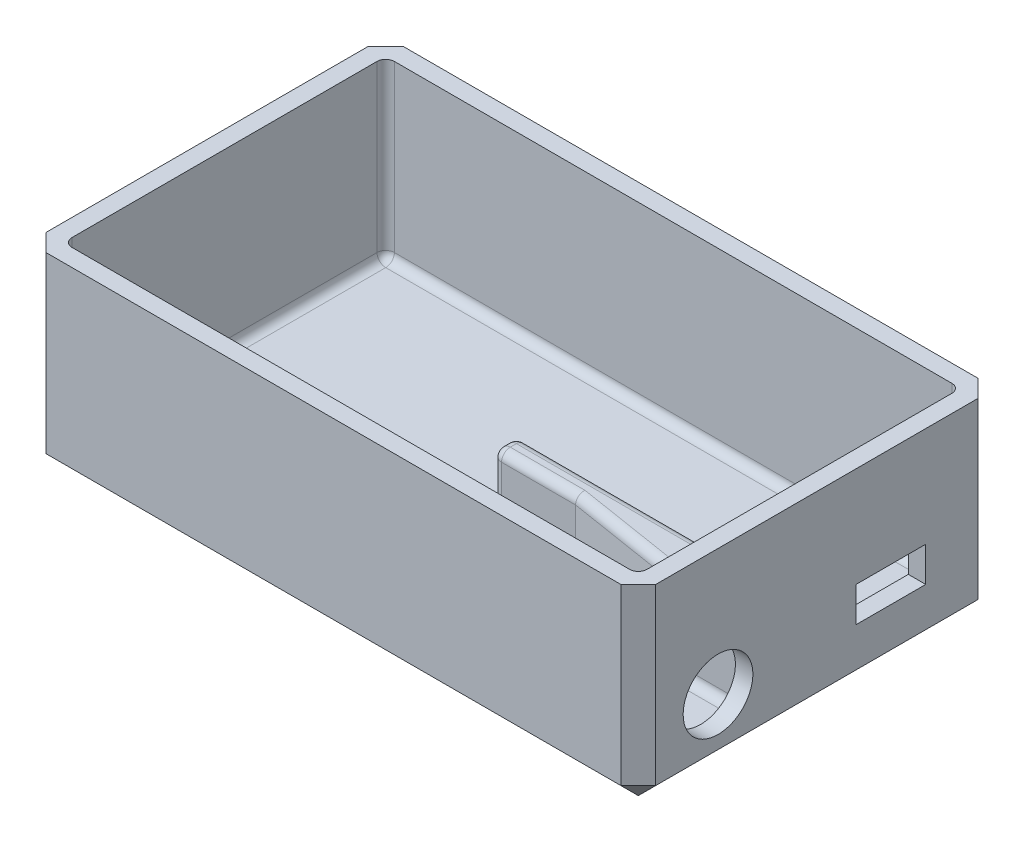
SolidWorks part; units mm, degrees
ref_plane "Plan de face" through (0, 0, 0) normal (0, 0, 1) x (1, 0, 0)
ref_plane "Plan de dessus" through (0, 0, 0) normal (0, 1, 0) x (1, 0, 0)
ref_plane "Plan de droite" through (0, 0, 0) normal (1, 0, 0) x (0, 0, -1)
sketch "Esquisse1" plane through (0, 0, 0) normal (0, 1, 0) x (1, 0, 0)
  line L1 (-35, 20.5) -> (35, 20.5)
  line L2 (-35, 20.5) -> (-35, -20.5)
  line L3 (-35, -20.5) -> (35, -20.5)
  line L4 (35, 20.5) -> (35, -20.5)
  line L5 (-35, 20.5) -> (35, -20.5) construction
  line L6 (-35, -20.5) -> (35, 20.5) construction
  point P0 (0, 0)
  dimension "D1" = 41
  dimension "D2" = 70
extrude "Boss.-Extru.1" add sketch "Esquisse1" along normal blind 22
shell "Coque1" thickness 2
sketch "Esquisse2" plane through (0, 2, 0) normal (0, 1, 0) x (1, 0, 0)
  line L0 (33, -16.5) -> (24, -16.5)
  line L1 (33, -18.5) -> (33, 18.5) construction
  line L2 (24, -16.5) -> (11.5, -18.5)
  line L3 (-33, -18.5) -> (33, -18.5) construction
  line L4 (11.5, -18.5) -> (33, -18.5)
  line L5 (33, -18.5) -> (33, -16.5)
  line L6 (33, -6.2) -> (24, -6.2)
  line L7 (24, -6.2) -> (11.5, -4.2)
  line L9 (33, -1.5) -> (33, -6.2)
  line L10 (11.5, -4.2) -> (2, -4.2)
  line L14 (2, -1.5) -> (33, -1.5)
  line L15 (2, -4.2) -> (2, -1.5)
  dimension "D1" = 14.3
  dimension "D2" = 10.3
  dimension "D3" = 2
  dimension "D4" = 4.7
  dimension "D5" = 9
  dimension "D6" = 9.5
  dimension "D7" = 31
extrude "Boss.-Extru.2" add sketch "Esquisse2" along normal blind 10
sketch "Esquisse3" plane through (33, 0, 0) normal (-1, 0, 0) x (0, 0, 1)
  line L0 (16.5, 2) -> (6.2, 2) construction
  line L1 (1.5, 2) -> (-18.5, 2) construction
  line L2 (-12.5, 6.5) -> (-4.5, 6.5)
  line L3 (-12.5, 6.5) -> (-12.5, 10.5)
  line L4 (-12.5, 10.5) -> (-4.5, 10.5)
  line L5 (-4.5, 6.5) -> (-4.5, 10.5)
  circle A0 centre (11.35, 7.5) radius 4
  point P4 (11.35, 2)
  point P11 (-8.5, 6.5)
  point P12 (-8.5, 2)
  dimension "D1" = 8
  dimension "D2" = 5.5
  dimension "D3" = 4.5
  dimension "D4" = 8
  dimension "D5" = 4
extrude "Enlèv. mat.-Extru.1" cut sketch "Esquisse3" against normal up to next
sketch "Esquisse4" plane through (-33, 0, 0) normal (1, 0, 0) x (0, 0, -1)
  circle A0 centre (-11.35, 7.5) radius 3.5
  circle A1 centre (-11.35, 7.5) radius 4 construction
  dimension "D1" = 7
extrude "Enlèv. mat.-Extru.2" cut sketch "Esquisse4" against normal up to next
fillet "Congé1" radius 1 29 edges at (28.5, 12, 6.2) (17.75, 12, 5.2) (6.75, 12, 4.2) (17.5, 12, 1.5) (2, 7, 4.2) (2, 7, 1.5) (22.25, 12, 18.5) (33, 12, 17.5) (33, 12, 3.85) (33, 7, 1.5) (28.5, 2, 16.5) (33, 7, 16.5) (33, 7, 6.2) (33, 17, 18.5) (33, 12, -18.5) (33, 2, 11.35) (17.75, 2, 17.5) (28.5, 2, 6.2) (17.75, 2, 5.2) (6.75, 2, 4.2) (17.5, 2, 1.5) (33, 2, -8.5) (-10.75, 2, 18.5) (-33, 12, 18.5) (-33, 2, 0) (0, 2, -18.5) (-33, 12, -18.5) (2, 2, 2.85) (2, 12, 2.85)
chamfer "Chanfrein1" distance 2 angle 45 8 edges at (0, 0, -20.5) (35, 11, -20.5) (35, 0, 0) (35, 11, 20.5) (0, 0, 20.5) (-35, 11, 20.5) (-35, 0, 0) (-35, 11, -20.5)
